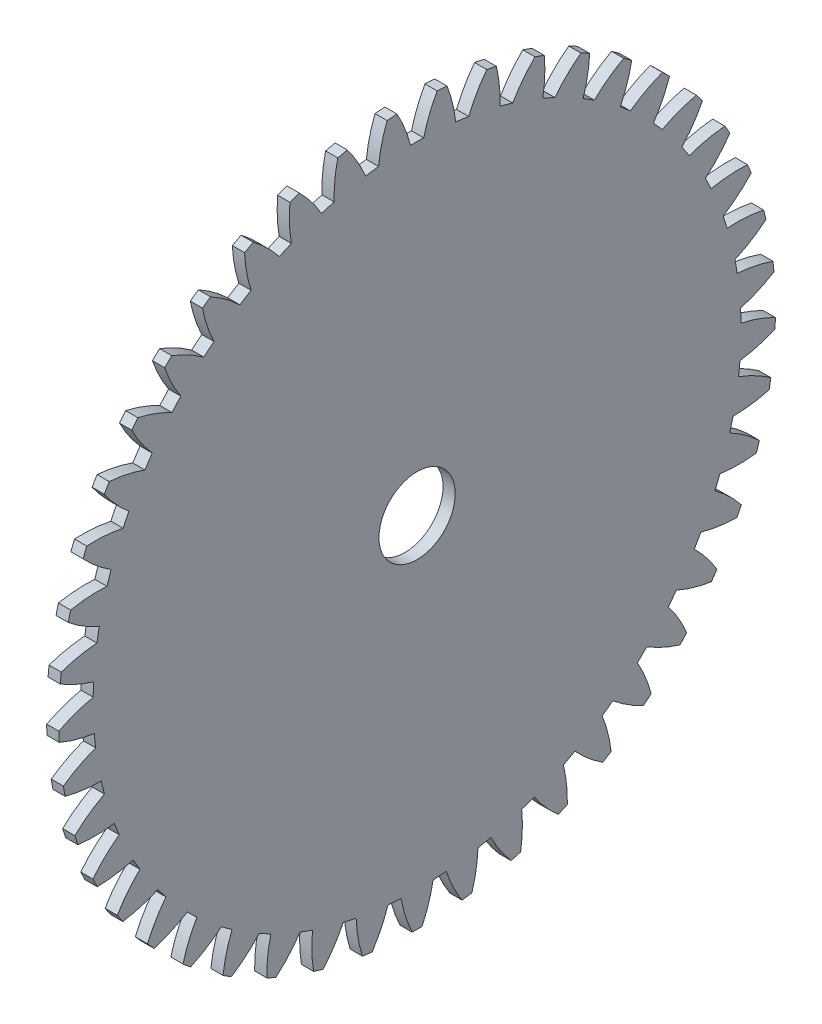
SolidWorks part; units mm, degrees
ref_plane "Plane1" through (0, 0, 0) normal (0, 0, 1) x (1, 0, 0)
ref_plane "Plane2" through (0, 0, 0) normal (0, 1, 0) x (1, 0, 0)
ref_plane "Plane3" through (0, 0, 0) normal (1, 0, 0) x (0, 0, -1)
sketch "HoldingSke" plane through (0, 0, 0) normal (0, 1, 0) x (1, 0, 0)
  line L0 (0, 0) -> (2.8284, -2.8284)
  line L1 (-15, 0) -> (100, 0) construction
  line L2 (0, 0) -> (-2.1039, 2.3779)
  line L3 (0, 0) -> (-11.863, 4.5341)
  line L4 (0, 0) -> (6.1066, 6.1066)
  line L5 (0, 0) -> (-46.8476, -17.4728)
  line L6 (0, 0) -> (-0.1658, -0.1119)
  line L7 (-2.1039, 2.3779) -> (8.6586, 51.2059)
  line L8 (-76.2, 54.61) -> (-76.1, 54.61)
  line L9 (-71.009, 38.7566) -> (-53.1078, 45.2721)
  line L10 (-76.2, 71.12) -> (104.1128, 71.12)
  line L11 (0, 0) -> (-0.2, 0)
  line L12 (-76.2, 101.6) -> (-76.192, 101.6)
  line L13 (24.9733, 27.94) -> (52.9518, 28.4284)
  line L14 (24.9733, 27.94) -> (24.9743, 27.94)
  line L15 (24.9733, 27.94) -> (100.4006, 29.5858)
  line L16 (-63.627, -0.25) -> (-12.827, -0.25)
  circle A0 centre (0, 0) radius 0.625
  circle A1 centre (0, 0) radius 5.3115
  circle A2 centre (0, 0) radius 37.5
  circle A3 centre (0, 0) radius 0.625
  dimension "MHD" = 10.623
  dimension "Hub_dia" = 75
  dimension "Bore" = 1.25
  dimension "MBD" = 1.25
  dimension "Num_teeth" = 45
  dimension "Pitch_radius" = 180.3128
  dimension "Pitch" = 4
  dimension "Width" = 0.2
  dimension "Overall_len" = 50
  dimension "Show_teeth" = 45
  dimension "Thickness" = 0.2
  dimension "OAL" = 50.0001
  dimension "T_dim" = 0.1
  dimension "Ap" = 20
  dimension "H" = 19.05
  dimension "Backlash" = 0.008
  dimension "Addendum_fac" = 1
  dimension "Dedendum_fac" = 1.25
  dimension "Clearance_fac" = 0.25
  dimension "Dedendum_add" = 0.001
  dimension "Module" = 0.25
sketch "BasProSke" plane through (0, 0, 0) normal (0, 1, 0) x (1, 0, 0)
  line L0 (-10, 0) -> (60, 0) construction
  line L1 (0, 0) -> (0, 5.875)
  line L2 (0, 0) -> (0.2, 0)
  line L3 (0.2, 0) -> (0.2, 5.875)
  line L4 (0.2, 5.875) -> (0, 5.875)
  dimension "Diameter" = 11.75
  dimension "Thickness" = 0.2
revolve "Base-Revolve" add sketch "BasProSke" angle 360 about L0
sketch "TooCutSke" plane through (0, 0, 0) normal (1, 0, 0) x (0, 0, -1)
  line L1 (0, 0) -> (0, 107) construction
  line L2 (0, 0) -> (-0.2103, 5.6211) construction
  line L3 (0, 0) -> (-0.7843, 11.2167) construction
  line L4 (-0.2103, 5.6211) -> (-0.3922, 5.6083) construction
  arc A0 (0.108, 5.3104) -> (-0.108, 5.3104) centre (0, 0) ccw
  arc A1 (0.343, 5.8904) -> (-0.343, 5.8904) centre (0, 0) ccw
  circle A2 centre (0, 0) radius 5.625 construction
  circle A3 centre (0, 0) radius 5.2858 construction
  arc A4 (-0.108, 5.3104) -> (-0.343, 5.8904) centre (-2.2906, 4.7637) ccw
  arc A5 (0.343, 5.8904) -> (0.108, 5.3104) centre (2.2906, 4.7637) ccw
  dimension "Root_dia" = 10.623
  dimension "Overcut_dia" = 11.8008
  dimension "Pitch_dia" = 11.25
  dimension "Base_dia" = 10.5715
  dimension "Flank_rad" = 2.25
  dimension "Half_ang" = 4
  dimension "Half_CT" = 0.1823
extrude "ToothCut" cut sketch "TooCutSke" along normal through all
fillet "Breaks" [suppressed] radius 0.005
fillet "RootFillets" [suppressed] radius 0.0635
pattern_circular "TeethCuts" count 45 every 8 about axis through (-10, 0, 0) along (1, 0, 0) of "ToothCut", "RootFillets", "Breaks"
sketch "HubNeaOneSke" plane through (0, 0, 0) normal (-1, 0, 0) x (0, 0, 1)
  circle A0 centre (0, 0) radius 5.3115
  dimension "Diameter" = 10.623
extrude "HubNearOne" [suppressed] add sketch "HubNeaOneSke" along normal blind 49.8001
sketch "HubNeaBotSke" plane through (0, 0, 0) normal (-1, 0, 0) x (0, 0, 1)
  circle A0 centre (0, 0) radius 5.3115
  dimension "Diameter" = 10.623
extrude "HubNearBoth" [suppressed] add sketch "HubNeaBotSke" along normal blind 24.9
ref_plane "FarPln" through (0.2, 0, 0) normal (1, 0, 0) x (0, 0, -1)
sketch "HubFarSke" plane through (0.2, 0, 0) normal (1, 0, 0) x (0, 0, -1)
  circle A0 centre (0, 0) radius 5.3115
  dimension "Diameter" = 10.623
extrude "HubFar" [suppressed] add sketch "HubFarSke" along normal blind 24.9
sketch "BorSke" plane through (0, 0, 0) normal (1, 0, 0) x (0, 0, -1)
  circle A0 centre (0, 0) radius 0.625
  dimension "Diameter" = 1.25
extrude "Bore" cut sketch "BorSke" along normal mid plane 100.0001
sketch "KeySke" plane through (0, 0, 0) normal (1, 0, 0) x (0, 0, -1)
  line L0 (-0.05, 0) -> (-0.05, 0.725)
  line L1 (-0.05, 0.725) -> (0.05, 0.725)
  line L2 (0.05, 0.725) -> (0.05, 0)
  line L3 (0, 0) -> (0, 34) construction
  line L4 (-0.05, 0) -> (0.05, 0)
  dimension "Offset" = 0.725
  dimension "Width" = 0.1
extrude "Keyway" [suppressed] cut sketch "KeySke" along normal mid plane 100.0001
pattern_circular "Keyway2" [suppressed] count 2 every 90 about axis through (-10, 0, 0) along (1, 0, 0)
equation "' \"Module@HoldingSke\" = 6.35"
equation "' \"Num_teeth@HoldingSke\" = 12"
equation "' \"Ap@HoldingSke\" =  20"
equation "' \"Width@HoldingSke\" = 0.5 * 25.4"
equation "' \"Hub_dia@HoldingSke\"= 1 * 25.4"
equation "' \"Overall_len@HoldingSke\" = 1.0 * 25.4"
equation "' \"Bore@HoldingSke\" = 0.75 * 25.4"
equation "' \"T_dim@HoldingSke\" = 0.1 * 25.4"
equation "' \"Width@KeySke\" = 0.25 * 25.4"
equation "' \"Show_teeth@HoldingSke\" = 13"
equation "' \"Backlash@HoldingSke\" = 0.009 * 25.4"
equation "' \"Addendum_fac@HoldingSke\" = 1.0"
equation "' \"Dedendum_fac@HoldingSke\" = 1.25"
equation "' \"Dedendum_add@HoldingSke\" = 0.00005 * 25.4"
equation "' \"Clearance_fac@HoldingSke\" = 0.25"
equation "\"Pitch@HoldingSke\" = 1 / \"Module@HoldingSke\""
equation "\"Overcut_dia@TooCutSke\" = (\"Num_teeth@HoldingSke\" + 2 * \"Addendum_fac@HoldingSke\") / \"Pitch@HoldingSke\" + 0.002 * 25.4"
equation "\"Pitch_dia@TooCutSke\" = \"Num_teeth@HoldingSke\" / \"Pitch@HoldingSke\""
equation "\"Base_dia@TooCutSke\" = \"Num_teeth@HoldingSke\" / \"Pitch@HoldingSke\" * cos((\"Ap@HoldingSke\"  * 3.14159265 / 180))"
equation "\"Root_dia@TooCutSke\" = (\"Num_teeth@HoldingSke\" + 2) / \"Pitch@HoldingSke\" - 2 * (\"Addendum_fac@HoldingSke\" + \"Dedendum_fac@HoldingSke\") / \"Pitch@HoldingSke\" - \"Dedendum_add@HoldingSke\" * 2"
equation "\"Half_ang@TooCutSke\" = 180 / \"Num_teeth@HoldingSke\""
equation "\"Half_CT@TooCutSke\" = \"Num_teeth@HoldingSke\" / \"Pitch@HoldingSke\" * sin((3.14159265 / 2 / \"Num_teeth@HoldingSke\")) / 2 - 7 * \"Backlash@HoldingSke\" / 4"
equation "\"Flank_rad@TooCutSke\" = \"Num_teeth@HoldingSke\" / \"Pitch@HoldingSke\" / 5"
equation "\"Radius@RootFillets\" = \"Clearance_fac@HoldingSke\" / \"Pitch@HoldingSke\" + \"Dedendum_add@HoldingSke\""
equation "\"Break_rad@Breaks\" = 0.02 / \"Pitch@HoldingSke\""
equation "\"Thickness@HoldingSke\" = \"Width@HoldingSke\""
equation "\"OAL@HoldingSke\" = \"Thickness@HoldingSke\""
equation "\"MHD@HoldingSke\" = (\"Num_teeth@HoldingSke\" + 2) / \"Pitch@HoldingSke\" - 2 * (\"Addendum_fac@HoldingSke\" + \"Dedendum_fac@HoldingSke\")  / \"Pitch@HoldingSke\" - \"Dedendum_add@HoldingSke\" * 2"
equation "\"MBD@HoldingSke\" = (\"Num_teeth@HoldingSke\" + 2) / \"Pitch@HoldingSke\" - 2 * (\"Addendum_fac@HoldingSke\" + \"Dedendum_fac@HoldingSke\")  / \"Pitch@HoldingSke\" - \"Dedendum_add@HoldingSke\" * 2 - 0.002 * 25.4"
equation "\"MHD@HoldingSke\" = ((sgn( \"MHD@HoldingSke\" - \"Hub_dia@HoldingSke\" )-1)*( \"MHD@HoldingSke\" - \"Hub_dia@HoldingSke\" ))/-2+ \"Hub_dia@HoldingSke\""
equation "\"MBD@HoldingSke\" = ((sgn( \"MBD@HoldingSke\" - \"Bore@HoldingSke\" )-1)*( \"MBD@HoldingSke\" - \"Bore@HoldingSke\" ))/-2+ \"Bore@HoldingSke\""
equation "\"OAL@HoldingSke\" = ((sgn( \"OAL@HoldingSke\" - \"Overall_len@HoldingSke\" )+1)*( \"OAL@HoldingSke\" - \"Overall_len@HoldingSke\" ))/2 + \"Overall_len@HoldingSke\" + 0.000002 * 25.4"
equation "\"Num_teeth@TeethCuts\" = int( \"Show_teeth@HoldingSke\" ) + 1"
equation "\"Num_teeth@TeethCuts\" = ((sgn( \"Num_teeth@TeethCuts\" - \"Num_teeth@HoldingSke\" )-1)*( \"Num_teeth@TeethCuts\" - \"Num_teeth@HoldingSke\" ))/-2+ \"Num_teeth@HoldingSke\""
equation "\"Num_teeth@TeethCuts\" = ((sgn( \"Num_teeth@TeethCuts\" - 2.0)+1)*( \"Num_teeth@TeethCuts\" - 2.0))/2 +2.0"
equation "\"Angle@TeethCuts\" = 360.0 / \"Num_teeth@HoldingSke\""
equation "\"Diameter@BasProSke\" = (\"Num_teeth@HoldingSke\" + 2 * \"Addendum_fac@HoldingSke\") / \"Pitch@HoldingSke\""
equation "\"Thickness@BasProSke\"  = \"Thickness@HoldingSke\""
equation "' \"Fillet_rad@BasProSke\" =  \"Thickness@HoldingSke\" * 0.05"
equation "\"MHD@HoldingSke\" = ((sgn( \"MHD@HoldingSke\" - \"Root_dia@TooCutSke\" )-1)*( \"MHD@HoldingSke\" - \"Root_dia@TooCutSke\" ))/-2+ \"Root_dia@TooCutSke\""
equation "\"Diameter@HubNeaOneSke\" = \"MHD@HoldingSke\""
equation "\"Length@HubNearOne\" = \"OAL@HoldingSke\" - \"Thickness@BasProSke\""
equation "\"Diameter@HubNeaBotSke\" = \"MHD@HoldingSke\""
equation "\"Length@HubNearBoth\" = ( \"OAL@HoldingSke\" - \"Thickness@BasProSke\" ) / 2.0"
equation "\"Thickness@FarPln\" = \"Thickness@BasProSke\""
equation "\"Diameter@HubFarSke\" = \"MHD@HoldingSke\""
equation "\"Length@HubFar\" = ( \"OAL@HoldingSke\" - \"Thickness@BasProSke\" ) / 2.0"
equation "\"Diameter@BorSke\" = \"MBD@HoldingSke\""
equation "\"D1@Bore\" = \"OAL@HoldingSke\" * 2.0"
equation "\"D1@Keyway\" = \"OAL@HoldingSke\" * 2.0"
equation "\"Offset@KeySke\" = \"T_dim@HoldingSke\" + \"MBD@HoldingSke\" / 2.0"
